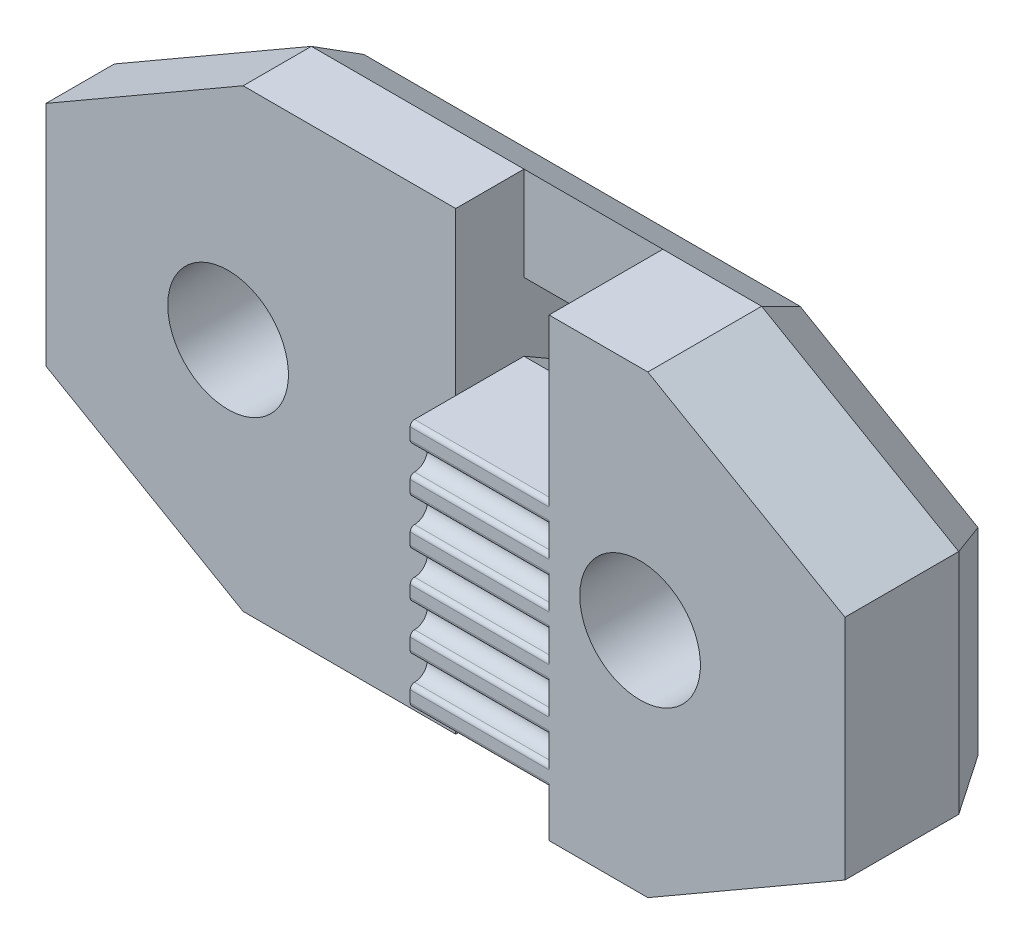
SolidWorks part; units mm, degrees
material "ABS"
ref_plane "Ebene vorne" through (0, 0, 0) normal (0, 0, 1) x (1, 0, 0)
ref_plane "Ebene oben" through (0, 0, 0) normal (0, 1, 0) x (1, 0, 0)
ref_plane "Ebene rechts" through (0, 0, 0) normal (1, 0, 0) x (0, 0, -1)
sketch "Skizze1" plane through (0, 0, 0) normal (0, 0, 1) x (1, 0, 0)
  line L0 (0, 0) -> (0, 9.44)
  line L1 (0, 9.44) -> (-7.24, 9.44) construction
  line L2 (-7.05, 10.19) -> (-7.05, 10.69)
  line L3 (-7.05, 8.69) -> (-7.05, 8.19)
  line L4 (-7.24, 10.88) -> (-9.24, 10.88)
  line L5 (-9.24, 10.88) -> (-9.24, 0)
  line L6 (-7.05, 6.69) -> (-7.05, 6.19)
  line L7 (-7.05, 4.69) -> (-7.05, 4.19)
  line L8 (-7.05, 2.69) -> (-7.05, 2.19)
  line L9 (-7.05, 0.69) -> (-7.05, 0.19)
  line L10 (-7.05, -1.31) -> (-7.05, -1.81) construction
  line L11 (-7.05, -3.31) -> (-7.05, -3.81) construction
  line L12 (-7.05, -5.31) -> (-7.05, -5.81) construction
  line L13 (-7.05, -7.31) -> (-7.05, -7.81) construction
  line L14 (-7.05, -9.31) -> (-7.05, -9.81) construction
  line L15 (-7.24, 0) -> (-9.24, 0)
  line L16 (0, 9.44) -> (0, 10.88)
  line L17 (0, 10.88) -> (-6, 10.88)
  line L18 (-6, 10.88) -> (-6, 0)
  line L19 (-6, 0) -> (0, 0)
  arc A0 (-7.24, 10) -> (-7.24, 8.88) centre (-7.24, 9.44) ccw
  arc A1 (-7.24, 8) -> (-7.24, 6.88) centre (-7.24, 7.44) ccw
  arc A2 (-7.05, 8.69) -> (-7.24, 8.88) centre (-7.24, 8.69) ccw
  arc A3 (-7.24, 8) -> (-7.05, 8.19) centre (-7.24, 8.19) ccw
  arc A4 (-7.05, 10.19) -> (-7.24, 10) centre (-7.24, 10.19) cw
  arc A5 (-7.24, 10.88) -> (-7.05, 10.69) centre (-7.24, 10.69) cw
  arc A6 (-7.24, 8) -> (-7.24, 6.88) centre (-7.24, 7.44) ccw
  arc A7 (-7.05, 6.69) -> (-7.24, 6.88) centre (-7.24, 6.69) ccw
  arc A8 (-7.24, 6) -> (-7.05, 6.19) centre (-7.24, 6.19) ccw
  arc A9 (-7.24, 6) -> (-7.24, 4.88) centre (-7.24, 5.44) ccw
  arc A10 (-7.05, 4.69) -> (-7.24, 4.88) centre (-7.24, 4.69) ccw
  arc A11 (-7.24, 4) -> (-7.05, 4.19) centre (-7.24, 4.19) ccw
  arc A12 (-7.24, 4) -> (-7.24, 2.88) centre (-7.24, 3.44) ccw
  arc A13 (-7.05, 2.69) -> (-7.24, 2.88) centre (-7.24, 2.69) ccw
  arc A14 (-7.24, 2) -> (-7.05, 2.19) centre (-7.24, 2.19) ccw
  arc A15 (-7.24, 2) -> (-7.24, 0.88) centre (-7.24, 1.44) ccw
  arc A16 (-7.05, 0.69) -> (-7.24, 0.88) centre (-7.24, 0.69) ccw
  arc A17 (-7.24, 0) -> (-7.05, 0.19) centre (-7.24, 0.19) ccw
  arc A18 (-7.24, 0) -> (-7.24, -1.12) centre (-7.24, -0.56) ccw construction
  arc A19 (-7.05, -1.31) -> (-7.24, -1.12) centre (-7.24, -1.31) ccw construction
  arc A20 (-7.24, -2) -> (-7.05, -1.81) centre (-7.24, -1.81) ccw construction
  arc A21 (-7.24, -2) -> (-7.24, -3.12) centre (-7.24, -2.56) ccw construction
  arc A22 (-7.05, -3.31) -> (-7.24, -3.12) centre (-7.24, -3.31) ccw construction
  arc A23 (-7.24, -4) -> (-7.05, -3.81) centre (-7.24, -3.81) ccw construction
  arc A24 (-7.24, -4) -> (-7.24, -5.12) centre (-7.24, -4.56) ccw construction
  arc A25 (-7.05, -5.31) -> (-7.24, -5.12) centre (-7.24, -5.31) ccw construction
  arc A26 (-7.24, -6) -> (-7.05, -5.81) centre (-7.24, -5.81) ccw construction
  arc A27 (-7.24, -6) -> (-7.24, -7.12) centre (-7.24, -6.56) ccw construction
  arc A28 (-7.05, -7.31) -> (-7.24, -7.12) centre (-7.24, -7.31) ccw construction
  arc A29 (-7.24, -8) -> (-7.05, -7.81) centre (-7.24, -7.81) ccw construction
  arc A30 (-7.24, -8) -> (-7.24, -9.12) centre (-7.24, -8.56) ccw construction
  arc A31 (-7.05, -9.31) -> (-7.24, -9.12) centre (-7.24, -9.31) ccw construction
  arc A32 (-7.24, -10) -> (-7.05, -9.81) centre (-7.24, -9.81) ccw construction
  point P6 (-7.8, 9.44)
  dimension "D1" = 0.56
  dimension "D3" = 0.75
  dimension "D2" = 2
  dimension "D5" = 2
  dimension "D6" = 1.8
  dimension "D7" = 6
  dimension "D8" = 10.88
  dimension "D4" = 10
extrude "Aufsatz-Linear austragen1" add sketch "Skizze1" along normal blind 6.1
sketch "Skizze2" plane through (0, 0, 6.1) normal (0, 0, 1) x (1, 0, 0)
  line L1 (-6, 10.88) -> (0, 10.88)
  line L2 (-6, 10.88) -> (-6, 0)
  line L3 (-6, 0) -> (0, 0)
  line L4 (0, 10.88) -> (0, 0)
extrude "Schnitt-Linear austragen1" cut sketch "Skizze2" against normal up to surface (6.1 mm away) up to face at (-3, 5.44, 0)
sketch "Skizze3" plane through (-9.24, 0, 0) normal (-1, 0, 0) x (0, 0, 1)
  line L0 (6.1, 0) -> (0, 0) construction
  line L1 (0, -2) -> (-13, -2)
  line L2 (0, -2) -> (0, 18)
  line L3 (0, 18) -> (-13, 18)
  line L4 (-13, -2) -> (-13, 18)
  line L5 (0, 10.88) -> (0, 0) construction
  line L6 (-4, 8) -> (0, 8) construction
  line L7 (6.1, 10.88) -> (6.1, 0) construction
  line L8 (0, 18) -> (6.1, 18)
  line L9 (0, 18) -> (0, 13.88)
  line L10 (0, 13.88) -> (6.1, 13.88)
  line L11 (6.1, 18) -> (6.1, 13.88)
  line L12 (6.1, 10.88) -> (0, 10.88) construction
  circle A0 centre (-4, 8) radius 2.65
  dimension "D4" = 5.3
  dimension "D1" = 20
  dimension "D2" = 2
  dimension "D3" = 4
  dimension "D5" = 13
  dimension "D6" = 3
extrude "Aufsatz-Linear austragen2" add sketch "Skizze3" against normal blind 2.19
sketch "Skizze4" plane through (-9.24, 0, 0) normal (-1, 0, 0) x (0, 0, 1)
  line L1 (6.1, 18) -> (24.1, 18)
  line L2 (6.1, 18) -> (6.1, -2)
  line L3 (6.1, -2) -> (24.1, -2)
  line L4 (24.1, 18) -> (24.1, -2)
  line L10 (6.1, 10.88) -> (0, 10.88)
  line L11 (0, 10.88) -> (0, 13.88)
  line L12 (0, 13.88) -> (6.1, 13.88)
  line L13 (6.1, 13.88) -> (6.1, 18)
  line L14 (6.1, 18) -> (-13, 18)
  line L15 (-13, 18) -> (-13, -2)
  line L16 (-13, -2) -> (0, -2)
  line L17 (0, -2) -> (0, 0)
  line L18 (0, 0) -> (6.1, 0)
  line L19 (6.1, 0) -> (6.1, 10.88)
  line L20 (6.1, 10.88) -> (0, 10.88)
  line L21 (0, 10.88) -> (0, 13.88)
  line L22 (0, 13.88) -> (6.1, 13.88)
  line L23 (6.1, 13.88) -> (6.1, 18)
  line L24 (6.1, 18) -> (-13, 18)
  line L25 (-13, 18) -> (-13, -2)
  line L26 (-13, -2) -> (0, -2)
  line L27 (0, -2) -> (0, 0)
  line L28 (0, 0) -> (6.1, 0)
  line L29 (6.1, 0) -> (6.1, 10.88)
  circle A0 centre (-4, 8) radius 2.65 construction
  circle A1 centre (-4, 8) radius 2.65
  circle A2 centre (16.1, 8) radius 2.65
  line M11 (6.1, 10.88) -> (0, 10.88)
  line M12 (0, 10.88) -> (0, 13.88)
  line M13 (0, 13.88) -> (6.1, 13.88)
  line M14 (6.1, 13.88) -> (6.1, 18)
  line M15 (6.1, 18) -> (-13, 18)
  line M16 (-13, 18) -> (-13, -2)
  line M17 (-13, -2) -> (0, -2)
  line M18 (0, -2) -> (0, 0)
  line M19 (0, 0) -> (6.1, 0)
  line M20 (6.1, 0) -> (6.1, 10.88)
  circle M21 centre (-4, 8) radius 2.65
  dimension "D2" = 10
  dimension "D3" = 8
  dimension "D1" = 0
extrude "Aufsatz-Linear austragen3" add sketch "Skizze4" along normal offset from surface (4.81 mm away) 7 contours L4 L1 L2 L3 A2 M14 M20 | M20 M11 M12 M13 M14 M15 M16 M17 M18 M19 M21 up to face at (-7.05, 6.344, 1.98)
sketch "Skizze5" plane through (-9.24, 0, 0) normal (1, 0, 0) x (0, 0, -1)
  line L7 (-6.1, 13.88) -> (-6.1, 18)
  line L8 (-6.1, 18) -> (-24.1, 18)
  line L9 (-24.1, 18) -> (-24.1, -2)
  line L10 (-24.1, -2) -> (-6.1, -2)
  line L11 (-6.1, -2) -> (-6.1, 0)
  line L12 (-6.1, 0) -> (-6.1, 10.88)
  line L13 (-6.1, 10.88) -> (-6.1, 13.88)
  line L14 (-6.1, 13.88) -> (-6.1, 18)
  line L15 (-6.1, 18) -> (-24.1, 18)
  line L16 (-24.1, 18) -> (-24.1, -2)
  line L17 (-24.1, -2) -> (-6.1, -2)
  line L18 (-6.1, -2) -> (-6.1, 0)
  line L19 (-6.1, 0) -> (-6.1, 10.88)
  line L20 (-6.1, 10.88) -> (-6.1, 13.88)
  circle A0 centre (-16.1, 8) radius 2.65 construction
  circle A1 centre (-16.1, 8) radius 2.65
  dimension "D1" = 0
extrude "Aufsatz-Linear austragen4" add sketch "Skizze5" along normal offset from surface (0.19 mm away) 2 up to face at (-7.05, 6.344, 1.98)
chamfer "Fase1" distance 5 angle 60 4 edges at (-10.55, 18, -13) (-11.55, 18, 24.1) (-11.55, -2, 24.1) (-10.55, -2, -13)
chamfer "Fase2" distance 2 angle 30 11 edges at (-14.05, 10.88, 3.05) (-14.05, 13.88, 3.05) (-14.05, -2, -2.1699) (-14.05, -2, 10.7699) (-14.05, 0.5, 19.7699) (-14.05, 8, 24.1) (-14.05, 15.5, 19.7699) (-14.05, 18, 5.55) (-14.05, 15.5, -8.6699) (-14.05, 8, -13) (-14.05, 0.5, -8.6699)
sketch "Skizze11" plane through (0, -2, 0) normal (0, -1, 0) x (1, 0, 0)
  line L0 (-14.05, 7.6) -> (-14.05, 6.1)
  line L1 (-14.05, 6.1) -> (-14.05, 15.1303) construction
  line L2 (-14.05, 0) -> (-14.05, -1.5)
  line L3 (-12.55, 1.5) -> (-12.55, 4.6)
  line L4 (-11.05, 1.5) -> (-11.05, 4.6)
  arc A0 (-14.05, 6.1) -> (-12.55, 4.6) centre (-14.05, 4.6) cw
  arc A1 (-14.05, 0) -> (-12.55, 1.5) centre (-14.05, 1.5) ccw
  arc A2 (-14.05, -1.5) -> (-11.05, 1.5) centre (-14.05, 1.5) ccw
  arc A3 (-14.05, 7.6) -> (-11.05, 4.6) centre (-14.05, 4.6) cw
  dimension "D1" = 1.5
  dimension "D2" = 1.5
extrude "Schnitt-Linear austragen3" cut sketch "Skizze11" against normal blind 2.5 from offset 4
sketch "Skizze12" plane through (0, 18, 0) normal (0, 1, 0) x (1, 0, 0)
  line L0 (-7.24, 0) -> (-12.05, 0) construction
  line L1 (-7.05, -6.1) -> (-12.05, -6.1)
  line L2 (-7.05, -6.1) -> (-7.05, 0)
  line L3 (-7.05, 0) -> (-12.05, 0)
  line L4 (-12.05, -6.1) -> (-12.05, 0)
  line L5 (-14.05, -15.1303) -> (-14.05, 4.0303) construction
  dimension "D1" = 2
  dimension "D2" = 5
extrude "Schnitt-Linear austragen4" cut sketch "Skizze12" against normal up to surface (4.12 mm away) up to face at (-9.45, 13.88, 3.66)
move or copy body "Körper-Verschieben/Kopieren1" bodies to move or copy 114 copy no rotation origin (-10.55, 0, 5.55) rotation axis (0, -1, 0) rotation angle 90
